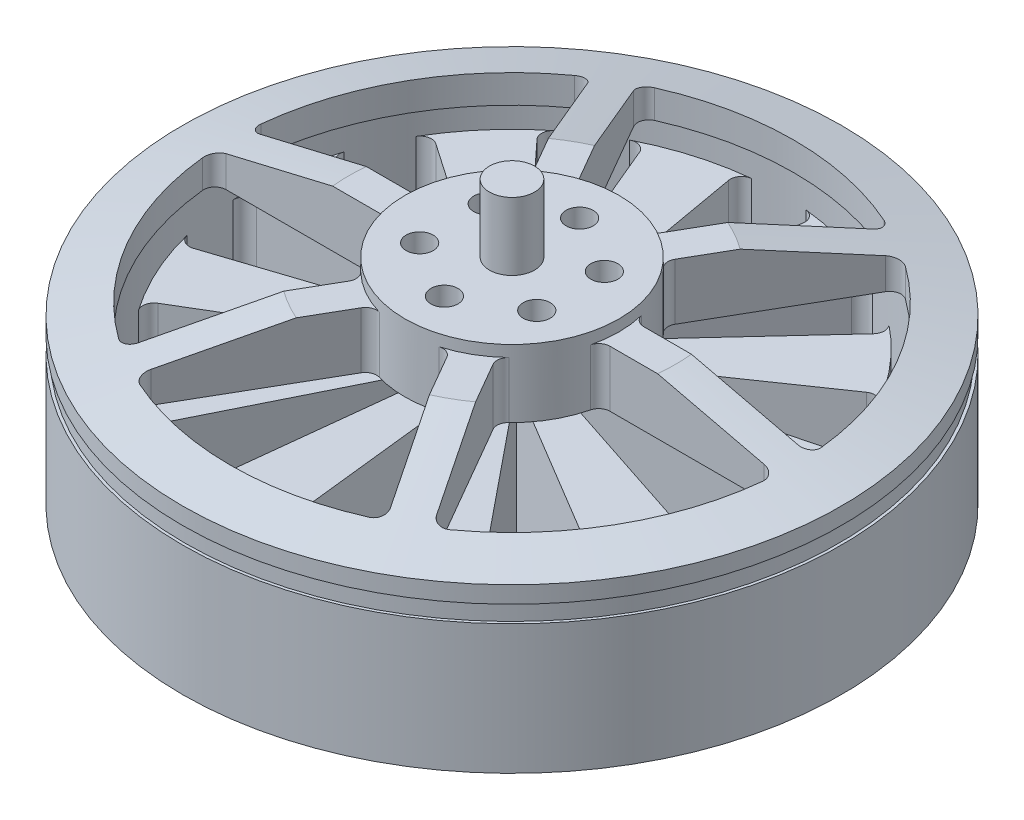
SolidWorks part; units mm, degrees
material "AISI 304"
ref_plane "前视基准面" through (0, 0, 0) normal (0, 0, 1) x (1, 0, 0)
ref_plane "上视基准面" through (0, 0, 0) normal (0, 1, 0) x (1, 0, 0)
ref_plane "右视基准面" through (0, 0, 0) normal (1, 0, 0) x (0, 0, -1)
sketch "Sketch1" plane through (0, 0, 0) normal (0, 1, 0) x (1, 0, 0)
  line L0 (0, 17.0731) -> (0, -17.4664) construction
  line L1 (-18.3889, 0) -> (24.4664, 0) construction
  line L2 (14.5, -3) -> (12.1347, -3)
  line L3 (2, 15.5) -> (-2, 15.5)
  line L4 (-3, 14.5) -> (-3, 12.1347)
  line L5 (3, 14.5) -> (3, 12.1347)
  line L6 (14.5, 3) -> (12.1347, 3)
  line L7 (15.5, -2) -> (15.5, 2)
  line L8 (-3, -14.5) -> (-3, -12.1347)
  line L9 (3, -14.5) -> (3, -12.1347)
  line L10 (-2, -15.5) -> (2, -15.5)
  line L11 (-14.5, 3) -> (-12.1347, 3)
  line L12 (-14.5, -3) -> (-12.1347, -3)
  line L13 (-15.5, 2) -> (-15.5, -2)
  arc A0 (-3, 12.1347) -> (-12.1347, 3) centre (0, 0) ccw
  circle A1 centre (0, 0) radius 6
  circle A2 centre (0, 12.5) radius 1.2
  arc A3 (3, 14.5) -> (2, 15.5) centre (2, 14.5) ccw
  arc A4 (-2, 15.5) -> (-3, 14.5) centre (-2, 14.5) ccw
  circle A5 centre (12.5, 0) radius 1.2
  arc A6 (15.5, 2) -> (14.5, 3) centre (14.5, 2) ccw
  arc A7 (14.5, -3) -> (15.5, -2) centre (14.5, -2) ccw
  circle A8 centre (0, -12.5) radius 1.2
  arc A9 (2, -15.5) -> (3, -14.5) centre (2, -14.5) ccw
  arc A10 (-3, -14.5) -> (-2, -15.5) centre (-2, -14.5) ccw
  circle A11 centre (-12.5, 0) radius 1.2
  arc A12 (-15.5, -2) -> (-14.5, -3) centre (-14.5, -2) ccw
  arc A13 (-14.5, 3) -> (-15.5, 2) centre (-14.5, 2) ccw
  arc A14 (-12.1347, -3) -> (-3, -12.1347) centre (0, 0) ccw
  arc A15 (12.1347, 3) -> (3, 12.1347) centre (0, 0) ccw
  arc A16 (3, -12.1347) -> (12.1347, -3) centre (0, 0) ccw
  circle A17 centre (0, 0) radius 8.5 construction
  arc A18 (-3, 7.953) -> (-7.953, 3) centre (0, 0) ccw construction
  arc A19 (-3.5647, 9.45) -> (-9.45, 3.5647) centre (0, 0) ccw
  arc A20 (-2.4353, 6.456) -> (-6.456, 2.4353) centre (0, 0) ccw
  arc A21 (-2.4353, 6.456) -> (-3.5647, 9.45) centre (-3, 7.953) ccw
  arc A22 (-9.45, 3.5647) -> (-6.456, 2.4353) centre (-7.953, 3) ccw
  arc A23 (7.953, 3) -> (3, 7.953) centre (0, 0) ccw construction
  arc A24 (9.45, 3.5647) -> (3.5647, 9.45) centre (0, 0) ccw
  arc A25 (6.456, 2.4353) -> (2.4353, 6.456) centre (0, 0) ccw
  arc A26 (6.456, 2.4353) -> (9.45, 3.5647) centre (7.953, 3) ccw
  arc A27 (3.5647, 9.45) -> (2.4353, 6.456) centre (3, 7.953) ccw
  arc A28 (3, -7.953) -> (7.953, -3) centre (0, 0) ccw construction
  arc A29 (3.5647, -9.45) -> (9.45, -3.5647) centre (0, 0) ccw
  arc A30 (2.4353, -6.456) -> (6.456, -2.4353) centre (0, 0) ccw
  arc A31 (2.4353, -6.456) -> (3.5647, -9.45) centre (3, -7.953) ccw
  arc A32 (9.45, -3.5647) -> (6.456, -2.4353) centre (7.953, -3) ccw
  arc A33 (-7.953, -3) -> (-3, -7.953) centre (0, 0) ccw construction
  arc A34 (-9.45, -3.5647) -> (-3.5647, -9.45) centre (0, 0) ccw
  arc A35 (-6.456, -2.4353) -> (-2.4353, -6.456) centre (0, 0) ccw
  arc A36 (-6.456, -2.4353) -> (-9.45, -3.5647) centre (-7.953, -3) ccw
  arc A37 (-3.5647, -9.45) -> (-2.4353, -6.456) centre (-3, -7.953) ccw
  point P16 (3, 15.5)
  point P19 (-3, 15.5)
  point P52 (0, 0)
  point P53 (-6.0104, 6.0104)
  point P63 (6.0104, 6.0104)
  point P70 (6.0104, -6.0104)
  point P77 (-6.0104, -6.0104)
  point P82 (0, 0)
  dimension "D1" = 25
  dimension "D2" = 12
  dimension "D5" = 2.4
  dimension "D6" = 1
  dimension "D9" = 17
  dimension "D12" = 1.6
  dimension "D3" = 15.5
  dimension "D4" = 6
  dimension "D7" = 12.5
  dimension "D10" = 3
  dimension "D11" = 3
  dimension "D8" = 4
  dimension "D13" = 4
extrude "Boss-Extrude1" add sketch "Sketch1" along normal blind 4.4
cosmetic thread "Cosmetic Thread1" parameters "D2"=3
cosmetic thread "Cosmetic Thread2" parameters "D2"=3
cosmetic thread "Cosmetic Thread3" parameters "D2"=3
cosmetic thread "Cosmetic Thread4" parameters "D2"=3
sketch "Sketch2" plane through (0, 4.4, 0) normal (0, 1, 0) x (1, 0, 0)
  arc A0 (-12.1347, -3) -> (-3, -12.1347) centre (0, 0) ccw
  arc A1 (-12.1347, -3) -> (-10.7247, -2.4457) centre (-12.5, 0) ccw
  arc A2 (-3, 12.1347) -> (-2.4457, 10.7247) centre (0, 12.5) ccw
  arc A3 (12.1347, 3) -> (10.7247, 2.4457) centre (12.5, 0) ccw
  arc A4 (3, -12.1347) -> (2.4457, -10.7247) centre (0, -12.5) ccw
  arc A5 (-3, 12.1347) -> (-12.1347, 3) centre (0, 0) ccw
  arc A6 (12.1347, 3) -> (3, 12.1347) centre (0, 0) ccw
  arc A7 (3, -12.1347) -> (12.1347, -3) centre (0, 0) ccw
  arc A8 (-10.7247, -2.4457) -> (-2.4457, -10.7247) centre (0, 0) ccw
  arc A9 (-2.4457, 10.7247) -> (-10.7247, 2.4457) centre (0, 0) ccw
  arc A10 (10.7247, 2.4457) -> (2.4457, 10.7247) centre (0, 0) ccw
  arc A11 (2.4457, -10.7247) -> (10.7247, -2.4457) centre (0, 0) ccw
  arc A12 (2.4457, 10.7247) -> (3, 12.1347) centre (0, 12.5) ccw
  arc A13 (10.7247, -2.4457) -> (12.1347, -3) centre (12.5, 0) ccw
  arc A14 (-2.4457, -10.7247) -> (-3, -12.1347) centre (0, -12.5) ccw
  arc A15 (-10.7247, 2.4457) -> (-12.1347, 3) centre (-12.5, 0) ccw
  point P18 (0, 0)
  dimension "D2" = 22
  dimension "D3" = 25
  dimension "D1" = 4
extrude "Boss-Extrude2" add sketch "Sketch2" along normal blind 4.4
sketch "Sketch3" plane through (0, 8.8, 0) normal (0, 1, 0) x (1, 0, 0)
  line L0 (-18.6186, 0) -> (21.8055, 0) construction
  line L1 (0, 15.9767) -> (0, -16.424) construction
  line L2 (-12.4789, 12.4789) -> (0, 0) construction
  line L3 (-8.4531, 7.0389) -> (-2.7071, 1.2929)
  line L4 (-7.0389, 8.4531) -> (-1.2929, 2.7071)
  line L5 (8.4531, 7.0389) -> (2.7071, 1.2929)
  line L6 (-13.186, 11.7718) -> (-0.7071, -0.7071) construction
  line L7 (-11.7718, 13.186) -> (0.7071, 0.7071) construction
  line L8 (7.0389, 8.4531) -> (1.2929, 2.7071)
  line L9 (7.0389, -8.4531) -> (1.2929, -2.7071)
  line L10 (8.4531, -7.0389) -> (2.7071, -1.2929)
  line L11 (-8.4531, -7.0389) -> (-2.7071, -1.2929)
  line L12 (-7.0389, -8.4531) -> (-1.2929, -2.7071)
  arc A0 (-2.7071, 1.2929) -> (-2.7071, -1.2929) centre (0, 0) ccw
  arc A1 (-7.0389, 8.4531) -> (-8.4531, 7.0389) centre (0, 0) ccw
  arc A2 (8.4531, 7.0389) -> (7.0389, 8.4531) centre (0, 0) ccw
  arc A3 (7.0389, -8.4531) -> (8.4531, -7.0389) centre (0, 0) ccw
  arc A4 (-8.4531, -7.0389) -> (-7.0389, -8.4531) centre (0, 0) ccw
  arc A5 (1.2929, 2.7071) -> (-1.2929, 2.7071) centre (0, 0) ccw
  arc A6 (2.7071, -1.2929) -> (2.7071, 1.2929) centre (0, 0) ccw
  arc A7 (-1.2929, -2.7071) -> (1.2929, -2.7071) centre (0, 0) ccw
  point P30 (0, 0)
  dimension "D1" = 6
  dimension "D5" = 22
  dimension "D2" = 45
  dimension "D3" = 1
  dimension "D4" = 1
  dimension "D6" = 4
extrude "Boss-Extrude3" add sketch "Sketch3" against normal blind 4.4
sketch "Sketch4" plane through (0, 4.4, 0) normal (0, -1, 0) x (1, 0, 0)
  circle A0 centre (0, 0) radius 3
extrude "Boss-Extrude4" add sketch "Sketch4" along normal blind 6
sketch "Sketch5" plane through (0, 8.8, 0) normal (0, 1, 0) x (1, 0, 0)
  circle A0 centre (0, 0) radius 2
  dimension "D1" = 4
extrude "Boss-Extrude5" add sketch "Sketch5" along normal blind 25
sketch "Sketch6" plane through (0, 0, 0) normal (0, 0, 1) x (1, 0, 0)
  line L0 (0, 28.4377) -> (0, -3.1922) construction
  line L1 (-25.25, 8.8) -> (-29.25, 8.8)
  line L3 (-29.25, 8.8) -> (-29.25, 23.3)
  line L4 (-29.25, 23.3) -> (-14.5, 26.8)
  line L5 (-14.5, 26.8) -> (-9.5, 26.8)
  line L6 (-9.5, 26.8) -> (-9.5, 27.8)
  line L7 (-9.5, 27.8) -> (0, 27.8)
  line L8 (-12.1347, 0) -> (-3, 0) construction
  line L10 (0, 27.8) -> (0, 21.8)
  line L11 (0, 21.8) -> (-25.25, 21.8)
  line L12 (-25.25, 21.8) -> (-25.25, 8.8)
  dimension "D1" = 27.8
  dimension "D2" = 9.5
  dimension "D3" = 5
  dimension "D4" = 29.25
  dimension "D5" = 1
  dimension "D6" = 14.5
  dimension "D7" = 4
  dimension "D8" = 6
revolve "Revolve2" add sketch "Sketch6" angle 360 about L0
sketch "Sketch7" plane through (0, 26.8, 0) normal (0, 1, 0) x (1, 0, 0)
  line L0 (-38.4586, 0) -> (33.9217, 0) construction
  line L1 (0, 30.0441) -> (0, -31.152) construction
  line L2 (-10.6357, 21.4215) -> (-3.8, 9.5818)
  line L3 (0, 0) -> (-16.9032, 29.2772) construction
  line L4 (0, 0) -> (16.9032, 29.2772) construction
  line L5 (10.6357, 21.4215) -> (3.8, 9.5818)
  line L6 (13.2338, 19.9215) -> (6.3981, 8.0818)
  line L7 (23.8694, 1.5) -> (10.198, 1.5)
  line L8 (23.8694, -1.5) -> (10.198, -1.5)
  line L9 (13.2338, -19.9215) -> (6.3981, -8.0818)
  line L10 (10.6357, -21.4215) -> (3.8, -9.5818)
  line L11 (-10.6357, -21.4215) -> (-3.8, -9.5818)
  line L12 (-13.2338, -19.9215) -> (-6.3981, -8.0818)
  line L13 (-23.8694, -1.5) -> (-10.198, -1.5)
  line L14 (-23.8694, 1.5) -> (-10.198, 1.5)
  line L15 (-13.2338, 19.9215) -> (-6.3981, 8.0818)
  arc A2 (10.1767, 22.8349) -> (-10.1767, 22.8349) centre (0, 0) ccw
  arc A3 (2.6545, 9.1216) -> (-2.6545, 9.1216) centre (0, 0) ccw
  arc A4 (-3.8, 9.5818) -> (-2.6545, 9.1216) centre (-2.934, 10.0818) ccw
  arc A5 (3.8, 9.5818) -> (2.6545, 9.1216) centre (2.934, 10.0818) cw
  arc A6 (10.6357, 21.4215) -> (10.1767, 22.8349) centre (9.7697, 21.9215) ccw
  arc A7 (-10.6357, 21.4215) -> (-10.1767, 22.8349) centre (-9.7697, 21.9215) cw
  arc A8 (13.2338, 19.9215) -> (14.6873, 20.2308) centre (14.0998, 19.4215) cw
  arc A9 (6.3981, 8.0818) -> (6.5723, 6.8597) centre (7.2641, 7.5818) ccw
  arc A10 (9.2268, 2.2619) -> (6.5723, 6.8597) centre (0, 0) ccw
  arc A11 (10.198, 1.5) -> (9.2268, 2.2619) centre (10.198, 2.5) cw
  arc A12 (23.8694, 1.5) -> (24.864, 2.6042) centre (23.8694, 2.5) ccw
  arc A13 (24.864, 2.6042) -> (14.6873, 20.2308) centre (0, 0) ccw
  arc A14 (23.8694, -1.5) -> (24.864, -2.6042) centre (23.8694, -2.5) cw
  arc A15 (10.198, -1.5) -> (9.2268, -2.2619) centre (10.198, -2.5) ccw
  arc A16 (6.5723, -6.8597) -> (9.2268, -2.2619) centre (0, 0) ccw
  arc A17 (6.3981, -8.0818) -> (6.5723, -6.8597) centre (7.2641, -7.5818) cw
  arc A18 (13.2338, -19.9215) -> (14.6873, -20.2308) centre (14.0998, -19.4215) ccw
  arc A19 (14.6873, -20.2308) -> (24.864, -2.6042) centre (0, 0) ccw
  arc A20 (10.6357, -21.4215) -> (10.1767, -22.8349) centre (9.7697, -21.9215) cw
  arc A21 (3.8, -9.5818) -> (2.6545, -9.1216) centre (2.934, -10.0818) ccw
  arc A22 (-2.6545, -9.1216) -> (2.6545, -9.1216) centre (0, 0) ccw
  arc A23 (-3.8, -9.5818) -> (-2.6545, -9.1216) centre (-2.934, -10.0818) cw
  arc A24 (-10.6357, -21.4215) -> (-10.1767, -22.8349) centre (-9.7697, -21.9215) ccw
  arc A25 (-10.1767, -22.8349) -> (10.1767, -22.8349) centre (0, 0) ccw
  arc A26 (-13.2338, -19.9215) -> (-14.6873, -20.2308) centre (-14.0998, -19.4215) cw
  arc A27 (-6.3981, -8.0818) -> (-6.5723, -6.8597) centre (-7.2641, -7.5818) ccw
  arc A28 (-9.2268, -2.2619) -> (-6.5723, -6.8597) centre (0, 0) ccw
  arc A29 (-10.198, -1.5) -> (-9.2268, -2.2619) centre (-10.198, -2.5) cw
  arc A30 (-23.8694, -1.5) -> (-24.864, -2.6042) centre (-23.8694, -2.5) ccw
  arc A31 (-24.864, -2.6042) -> (-14.6873, -20.2308) centre (0, 0) ccw
  arc A32 (-23.8694, 1.5) -> (-24.864, 2.6042) centre (-23.8694, 2.5) cw
  arc A33 (-10.198, 1.5) -> (-9.2268, 2.2619) centre (-10.198, 2.5) ccw
  arc A34 (-6.5723, 6.8597) -> (-9.2268, 2.2619) centre (0, 0) ccw
  arc A35 (-6.3981, 8.0818) -> (-6.5723, 6.8597) centre (-7.2641, 7.5818) cw
  arc A36 (-13.2338, 19.9215) -> (-14.6873, 20.2308) centre (-14.0998, 19.4215) ccw
  arc A37 (-14.6873, 20.2308) -> (-24.864, 2.6042) centre (0, 0) ccw
  point P12 (-3.3914, 8.874)
  point P17 (3.3914, 8.874)
  point P85 (0, 0)
  dimension "D1" = 25
  dimension "D2" = 9.5
  dimension "D7" = 1
  dimension "D3" = 1.5
  dimension "D4" = 30
  dimension "D5" = 30
  dimension "D6" = 6.7828
  dimension "D8" = 6
extrude "Cut-Extrude1" cut sketch "Sketch7" against normal blind 19
sketch "Sketch8" plane through (0, 0, 0) normal (0, 0, 1) x (1, 0, 0)
  line L0 (0, 34.8317) -> (0, -3.8139) construction
  line L1 (0, 20.8) -> (-23.8, 20.8)
  line L2 (-23.8, 20.8) -> (-23.8, 8.8)
  line L3 (-25.25, 8.8) -> (25.25, 8.8) construction
  line L4 (-23.8, 8.8) -> (0, 8.8)
  line L5 (0, 20.8) -> (0, 8.8)
  dimension "D1" = 12
  dimension "D2" = 23.8
revolve "Revolve3" add sketch "Sketch8" angle 360 about L0
sketch "Sketch9" plane through (0, 20.8, 0) normal (0, 1, 0) x (1, 0, 0)
  line L0 (0, 24.4521) -> (0, 3.8491) construction
  line L1 (-3.2903, 22.5095) -> (0, 3.8491)
  line L2 (3.2903, 22.5095) -> (0, 3.8491)
  line L3 (9.4015, 20.7151) -> (2.081, 3.2381)
  line L4 (14.9375, 17.1573) -> (2.081, 3.2381)
  line L5 (19.1085, 12.3438) -> (3.5013, 1.599)
  line L6 (21.8422, 6.3578) -> (3.5013, 1.599)
  line L7 (22.7486, 0.0534) -> (3.8099, -0.5478)
  line L8 (21.8121, -6.4603) -> (3.8099, -0.5478)
  line L9 (19.1662, -12.2539) -> (2.9089, -2.5206)
  line L10 (14.8568, -17.2272) -> (2.9089, -2.5206)
  line L11 (9.4987, -20.6707) -> (1.0844, -3.6932)
  line L12 (3.1846, -22.5247) -> (1.0844, -3.6932)
  line L13 (-3.1846, -22.5247) -> (-1.0844, -3.6932)
  line L14 (-9.4987, -20.6707) -> (-1.0844, -3.6932)
  line L15 (-14.8568, -17.2272) -> (-2.9089, -2.5206)
  line L16 (-19.1662, -12.2539) -> (-2.9089, -2.5206)
  line L17 (-21.8121, -6.4603) -> (-3.8099, -0.5478)
  line L18 (-22.7486, 0.0534) -> (-3.8099, -0.5478)
  line L19 (-21.8422, 6.3578) -> (-3.5013, 1.599)
  line L20 (-19.1085, 12.3438) -> (-3.5013, 1.599)
  line L21 (-14.9375, 17.1573) -> (-2.081, 3.2381)
  line L22 (-9.4015, 20.7151) -> (-2.081, 3.2381)
  circle A0 centre (0, 0) radius 23.8 construction
  arc A1 (2.4066, 23.678) -> (-2.4066, 23.678) centre (0, 0) ccw
  arc A2 (3.2903, 22.5095) -> (2.4066, 23.678) centre (2.3055, 22.6831) ccw
  arc A3 (-3.2903, 22.5095) -> (-2.4066, 23.678) centre (-2.3055, 22.6831) cw
  arc A4 (14.8259, 18.6181) -> (10.7767, 21.2203) centre (0, 0) ccw
  arc A5 (9.4015, 20.7151) -> (10.7767, 21.2203) centre (10.3239, 20.3287) cw
  arc A6 (14.9375, 17.1573) -> (14.8259, 18.6181) centre (14.203, 17.8358) ccw
  arc A7 (22.538, 7.647) -> (20.5385, 12.0254) centre (0, 0) ccw
  arc A8 (19.1085, 12.3438) -> (20.5385, 12.0254) centre (19.6756, 11.5201) cw
  arc A9 (21.8422, 6.3578) -> (22.538, 7.647) centre (21.5911, 7.3257) ccw
  arc A10 (23.0945, -5.7519) -> (23.7795, -0.9876) centre (0, 0) ccw
  arc A11 (22.7486, 0.0534) -> (23.7795, -0.9876) centre (22.7804, -0.9461) cw
  arc A12 (21.8121, -6.4603) -> (23.0945, -5.7519) centre (22.1241, -5.5102) ccw
  arc A13 (16.3186, -17.3246) -> (19.4707, -13.687) centre (0, 0) ccw
  arc A14 (19.1662, -12.2539) -> (19.4707, -13.687) centre (18.6526, -13.1119) cw
  arc A15 (14.8568, -17.2272) -> (16.3186, -17.3246) centre (15.633, -16.5967) ccw
  arc A16 (4.3617, -23.3969) -> (8.98, -22.0409) centre (0, 0) ccw
  arc A17 (9.4987, -20.6707) -> (8.98, -22.0409) centre (8.6027, -21.1148) cw
  arc A18 (3.1846, -22.5247) -> (4.3617, -23.3969) centre (4.1784, -22.4138) ccw
  arc A19 (-8.98, -22.0409) -> (-4.3617, -23.3969) centre (0, 0) ccw
  arc A20 (-3.1846, -22.5247) -> (-4.3617, -23.3969) centre (-4.1784, -22.4138) cw
  arc A21 (-9.4987, -20.6707) -> (-8.98, -22.0409) centre (-8.6027, -21.1148) ccw
  arc A22 (-19.4707, -13.687) -> (-16.3186, -17.3246) centre (0, 0) ccw
  arc A23 (-14.8568, -17.2272) -> (-16.3186, -17.3246) centre (-15.633, -16.5967) cw
  arc A24 (-19.1662, -12.2539) -> (-19.4707, -13.687) centre (-18.6526, -13.1119) ccw
  arc A25 (-23.7795, -0.9876) -> (-23.0945, -5.7519) centre (0, 0) ccw
  arc A26 (-21.8121, -6.4603) -> (-23.0945, -5.7519) centre (-22.1241, -5.5102) cw
  arc A27 (-22.7486, 0.0534) -> (-23.7795, -0.9876) centre (-22.7804, -0.9461) ccw
  arc A28 (-20.5385, 12.0254) -> (-22.538, 7.647) centre (0, 0) ccw
  arc A29 (-21.8422, 6.3578) -> (-22.538, 7.647) centre (-21.5911, 7.3257) cw
  arc A30 (-19.1085, 12.3438) -> (-20.5385, 12.0254) centre (-19.6756, 11.5201) ccw
  arc A31 (-10.7767, 21.2203) -> (-14.8259, 18.6181) centre (0, 0) ccw
  arc A32 (-14.9375, 17.1573) -> (-14.8259, 18.6181) centre (-14.203, 17.8358) cw
  arc A33 (-9.4015, 20.7151) -> (-10.7767, 21.2203) centre (-10.3239, 20.3287) ccw
  point P12 (3.473, 23.5452)
  point P15 (-3.473, 23.5452)
  point P87 (0, 0)
  dimension "D3" = 1
  dimension "D1" = 10
  dimension "D2" = 20
  dimension "D4" = 11
extrude "Cut-Extrude2" cut sketch "Sketch9" against normal blind 12 contours A1 A3 L1 L2 A2 | L3 L4 A6 A4 A5 | L5 L6 A9 A7 A8 | L7 L8 A12 A10 A11 | L9 L10 A15 A13 A14 | L11 L12 A18 A16 A17 | L13 L14 A21 A19 A20 | L15 L16 A24 A22 A23 | L17 L18 A27 A25 A26 | L19 L20 A30 A28 A29 | L21 L22 A33 A31 A32
sketch "Sketch10" plane through (0, 27.8, 0) normal (0, 1, 0) x (1, 0, 0)
  circle A0 centre (0, 0) radius 6 construction
  circle A1 centre (0, 6) radius 1.2
  circle A2 centre (5.1962, 3) radius 1.2
  circle A3 centre (5.1962, -3) radius 1.2
  circle A4 centre (0, -6) radius 1.2
  circle A5 centre (-5.1962, -3) radius 1.2
  circle A6 centre (-5.1962, 3) radius 1.2
  point P17 (0, 0)
  dimension "D1" = 12
  dimension "D2" = 2.4
  dimension "D4" = 12
  dimension "D3" = 6
extrude "Cut-Extrude3" cut sketch "Sketch10" against normal blind 6
cosmetic thread "Cosmetic Thread5" parameters "D2"=3
cosmetic thread "Cosmetic Thread6" parameters "D2"=3
cosmetic thread "Cosmetic Thread7" parameters "D2"=3
cosmetic thread "Cosmetic Thread8" parameters "D2"=3
cosmetic thread "Cosmetic Thread9" parameters "D2"=3
cosmetic thread "Cosmetic Thread10" parameters "D2"=3
sketch "Sketch11" plane through (0, 0, 0) normal (0, 0, 1) x (1, 0, 0)
  line L0 (0, 34.7094) -> (0, -4.9961) construction
  line L1 (-31, 21.8) -> (-29, 21.8)
  line L2 (-29, 21.8) -> (-29, 20.3)
  line L3 (-29, 20.3) -> (-31, 20.3)
  line L4 (-31, 20.3) -> (-31, 21.8)
  line L5 (2, 33.8) -> (-2, 33.8) construction
  dimension "D1" = 29
  dimension "D2" = 2
  dimension "D3" = 1.5
  dimension "D4" = 12
revolve "Cut-Revolve1" cut sketch "Sketch11" angle 360 about L0
